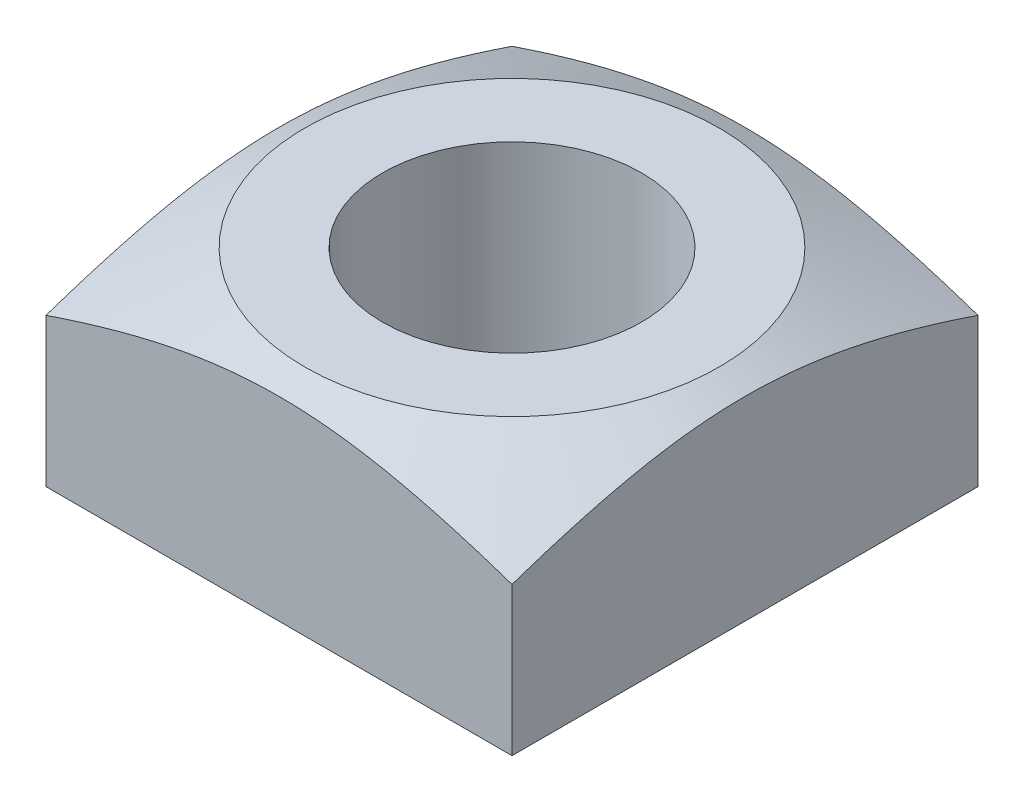
SolidWorks part; units mm, degrees
material "Galvanized Steel"
ref_plane "Front Plane" through (0, 0, 0) normal (0, 0, 1) x (1, 0, 0)
ref_plane "Top Plane" through (0, 0, 0) normal (0, 1, 0) x (1, 0, 0)
ref_plane "Right Plane" through (0, 0, 0) normal (1, 0, 0) x (0, 0, -1)
sketch "Sketch1" plane through (0, 0, 0) normal (0, 1, 0) x (1, 0, 0)
  line L1 (2.7, -2.7) -> (-2.7, -2.7)
  line L2 (2.7, -2.7) -> (2.7, 2.7)
  line L3 (2.7, 2.7) -> (-2.7, 2.7)
  line L4 (-2.7, -2.7) -> (-2.7, 2.7)
  line L5 (2.7, -2.7) -> (-2.7, 2.7) construction
  line L6 (2.7, 2.7) -> (-2.7, -2.7) construction
  circle A0 centre (0, 0) radius 1.5
  dimension "D2" = 3
  dimension "D1" = 5.4
extrude "Boss-Extrude1" add sketch "Sketch1" along normal blind 2.4
sketch "Sketch2" plane through (0, 0, 0) normal (0, 0, 1) x (1, 0, 0)
  line L0 (-2.4, 2.4) -> (-4.9, 1.2)
  line L1 (-2.7, 2.4) -> (2.7, 2.4) construction
  line L2 (-4.9, 1.2) -> (-4.9, 2.4)
  line L3 (-4.9, 2.4) -> (-2.4, 2.4)
  dimension "D1" = 2.4
  dimension "D2" = 1.2
  dimension "D3" = 2.5
ref_axis "Axis1" through (0, 2.4, 0) along (0, -1, 0)
revolve "Cut-Revolve1" cut sketch "Sketch2" angle 360 about axis through (0, 2.4, 0) along (0, -1, 0)
